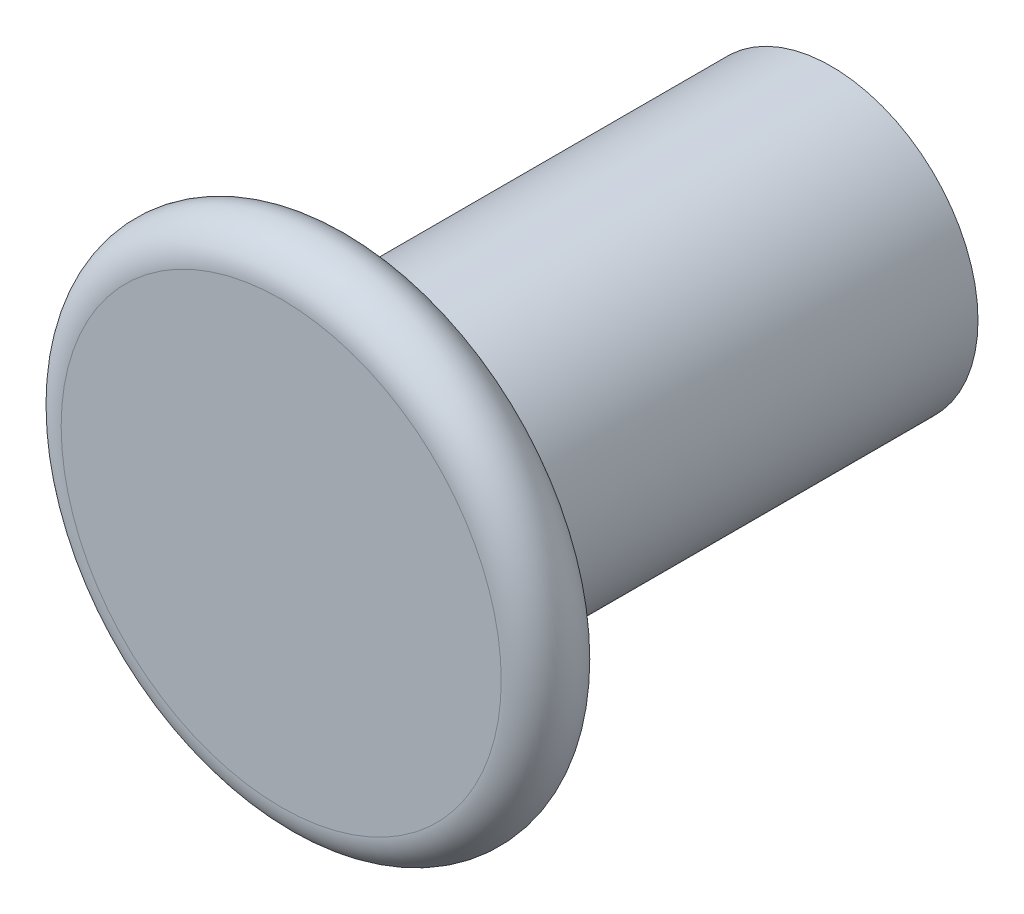
SolidWorks part; units mm, degrees
ref_plane "前视基准面" through (0, 0, 0) normal (0, 0, 1) x (1, 0, 0)
ref_plane "上视基准面" through (0, 0, 0) normal (0, 1, 0) x (1, 0, 0)
ref_plane "右视基准面" through (0, 0, 0) normal (1, 0, 0) x (0, 0, -1)
sketch "草图1" plane through (0, 0, 0) normal (0, 0, 1) x (1, 0, 0)
  circle A0 centre (0, 0) radius 20
  dimension "D1" = 40
extrude "凸台-拉伸1" add sketch "草图1" along normal blind 60
sketch "草图2" plane through (0, 0, 60) normal (0, 0, 1) x (1, 0, 0)
  circle A0 centre (0, 0) radius 10
  dimension "D1" = 20
extrude "凸台-拉伸2" add sketch "草图2" along normal blind 5
sketch "草图3" plane through (0, 0, 0) normal (1, 0, 0) x (0, 0, -1)
  line L0 (-65, 10) -> (-65, -10) construction
  line L1 (-65, 0) -> (-75, 0)
  line L2 (-65, 0) -> (-65, 30)
  line L3 (-65, 30) -> (-75, 30) construction
  line L4 (-75, 0) -> (-75, 30)
  arc A0 (-65, 30) -> (-75, 30) centre (-70, 30) ccw
  dimension "D2" = 5
  dimension "D1" = 30
revolve "旋转1" add sketch "草图3" angle 360 about L1
